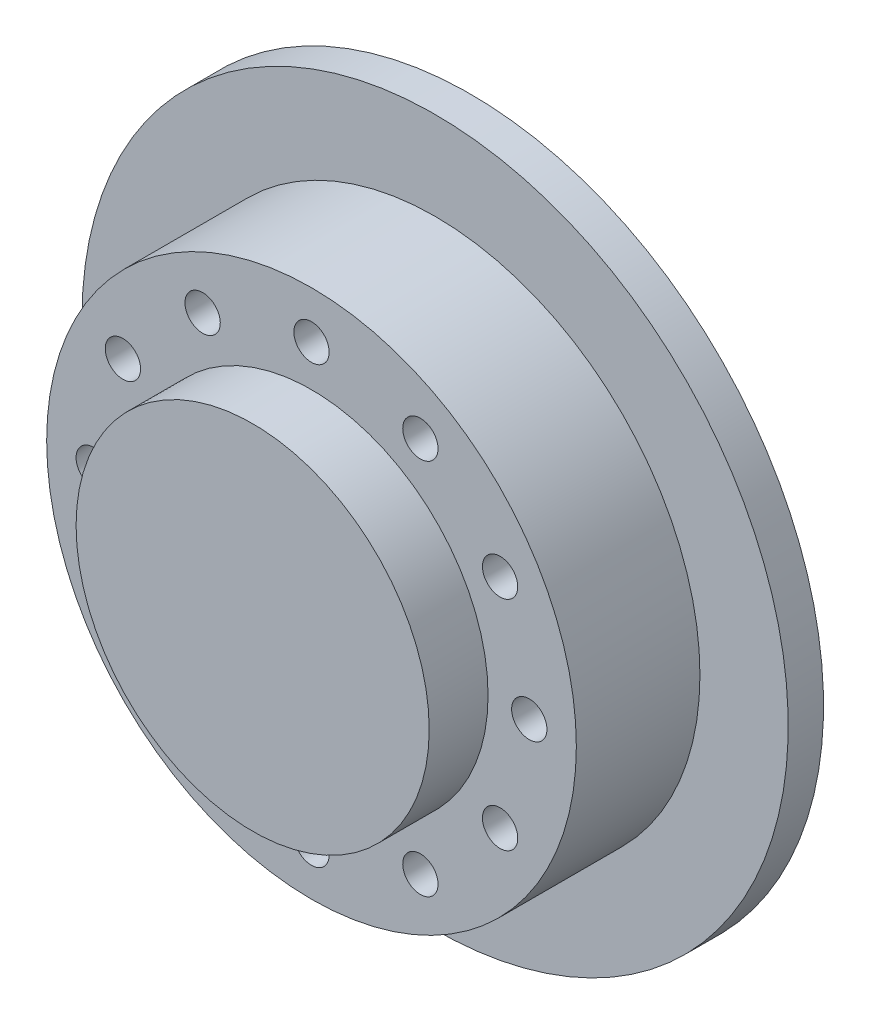
SolidWorks part; units mm, degrees
ref_plane "前视基准面" through (0, 0, 0) normal (0, 0, 1) x (1, 0, 0)
ref_plane "上视基准面" through (0, 0, 0) normal (0, 1, 0) x (1, 0, 0)
ref_plane "右视基准面" through (0, 0, 0) normal (1, 0, 0) x (0, 0, -1)
other "Configuration Table"
sketch "草图1" plane through (0, 0, 0) normal (0, 0, 1) x (1, 0, 0)
  circle A0 centre (0, 0) radius 22.5
  dimension "D1" = 45
extrude "凸台-拉伸1" add sketch "草图1" along normal blind 13.5
sketch "草图2" plane through (0, 0, 13.5) normal (0, 0, 1) x (1, 0, 0)
  circle A0 centre (0, 0) radius 15
  dimension "D1" = 30
extrude "凸台-拉伸2" add sketch "草图2" along normal blind 5
sketch "草图3" plane through (0, 0, 13.5) normal (0, 0, 1) x (1, 0, 0)
  circle A0 centre (0, 0) radius 18.5 construction
  circle A1 centre (0, 18.5) radius 1.5
  dimension "D1" = 37
  dimension "D2" = 3
extrude "切除-拉伸1" cut sketch "草图3" against normal blind 5
sketch "草图5" plane through (0, 0, 13.5) normal (0, 0, 1) x (1, 0, 0)
  circle A0 centre (0, 18.5) radius 1.5
  dimension "D1" = 3
extrude "切除-拉伸2" cut sketch "草图5" against normal through all
sketch "草图9" plane through (0, 0, 0) normal (0, 0, -1) x (-1, 0, 0)
  line L1 (1.314, 21.7052) -> (-2.1188, 21.2406)
  line L2 (-2.1188, 21.2406) -> (-3.4328, 18.0353)
  line L3 (-3.4328, 18.0353) -> (-1.314, 15.2948)
  line L4 (-1.314, 15.2948) -> (2.1188, 15.7594)
  line L5 (2.1188, 15.7594) -> (3.4328, 18.9647)
  line L6 (3.4328, 18.9647) -> (1.314, 21.7052)
  circle A0 centre (0, 18.5) radius 3 construction
  dimension "D1" = 6
extrude "切除-拉伸6" cut sketch "草图9" against normal blind 3
pattern_circular "阵列(圆周)1" count 12 over 360 about axis through (0, 0, 0) along (0, 0, 1) of "切除-拉伸1", "切除-拉伸6", "切除-拉伸2"
sketch "草图10" plane through (0, 0, 0) normal (0, 0, -1) x (-1, 0, 0)
  circle A0 centre (0, 0) radius 22.5
  circle A1 centre (0, 0) radius 30
  circle A2 centre (0, 0) radius 22.5 construction
  dimension "D1" = 60
extrude "凸台-拉伸3" add sketch "草图10" against normal blind 3 separate body
